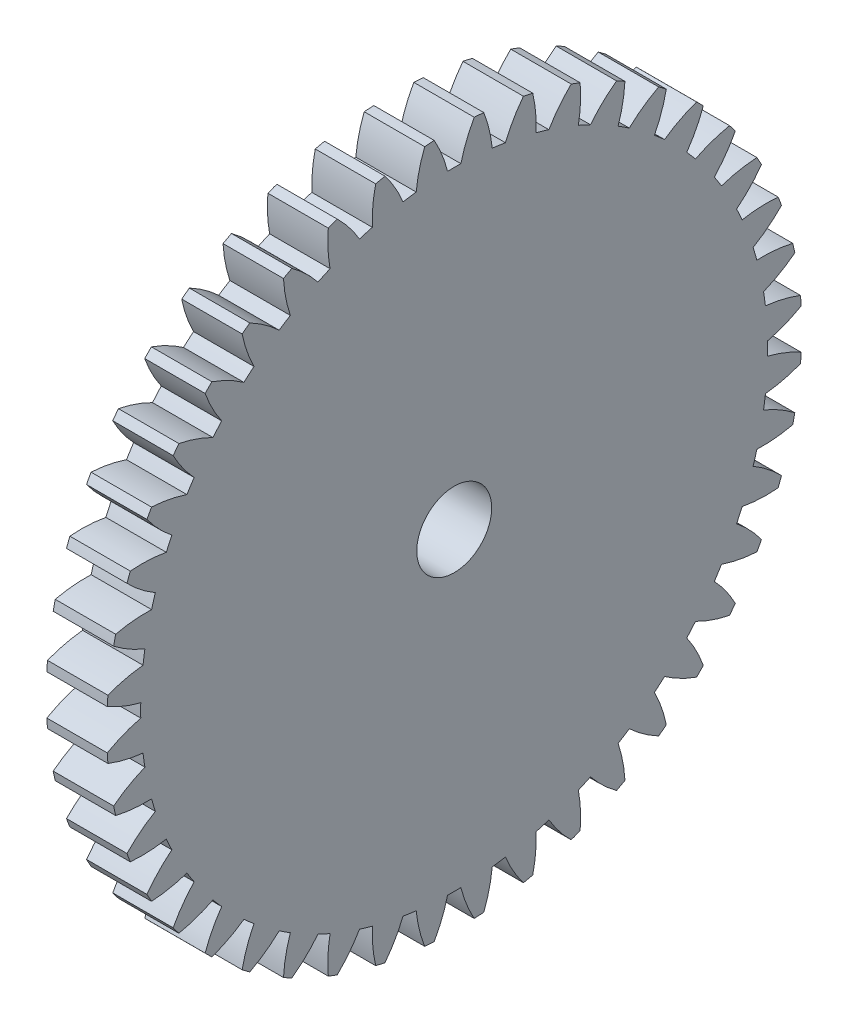
SolidWorks part; units mm, degrees
ref_plane "Front Plane" through (0, 0, 0) normal (0, 0, 1) x (1, 0, 0)
ref_plane "Top Plane" through (0, 0, 0) normal (0, 1, 0) x (1, 0, 0)
ref_plane "Right Plane" through (0, 0, 0) normal (1, 0, 0) x (0, 0, -1)
ref_plane "Plane1" through (3.175, 0, 0) normal (1, 0, 0) x (0, 0, -1)
sketch "Sketch1" plane through (3.175, 0, 0) normal (1, 0, 0) x (0, 0, -1)
  circle A0 centre (-15.8569, 4.6894) radius 0.3969
  arc A1 (-52.3087, 6.7937) -> (-48.7889, 5.3886) centre (-45.4175, 18.9457) ccw
  arc A2 (-48.7889, 5.3886) -> (-48.7889, 3.9902) centre (-15.8569, 4.6894) ccw
  arc A3 (-48.7889, 3.9902) -> (-52.3087, 2.5851) centre (-45.4175, -9.5669) ccw
  arc A4 (-52.3087, 2.5851) -> (-52.2372, 1.5846) centre (-15.8569, 4.6894) ccw
  arc A5 (-52.2372, 1.5846) -> (-48.5532, 0.6948) centre (-47.1455, 14.5937) ccw
  arc A6 (-48.5532, 0.6948) -> (-48.3541, -0.6894) centre (-15.8569, 4.6894) ccw
  arc A7 (-48.3541, -0.6894) -> (-51.6382, -2.5811) centre (-43.0877, -13.6287) ccw
  arc A8 (-51.6382, -2.5811) -> (-51.425, -3.5612) centre (-15.8569, 4.6894) ccw
  arc A9 (-51.425, -3.5612) -> (-47.6519, -3.9177) centre (-48.2366, 10.0401) ccw
  arc A10 (-47.6519, -3.9177) -> (-47.2579, -5.2595) centre (-15.8569, 4.6894) ccw
  arc A11 (-47.2579, -5.2595) -> (-50.2393, -7.5993) centre (-40.2036, -17.3176) ccw
  arc A12 (-50.2393, -7.5993) -> (-49.8888, -8.5391) centre (-15.8569, 4.6894) ccw
  arc A13 (-49.8888, -8.5391) -> (-46.1033, -8.355) centre (-48.6685, 5.3775) ccw
  arc A14 (-46.1033, -8.355) -> (-45.5224, -9.6271) centre (-15.8569, 4.6894) ccw
  arc A15 (-45.5224, -9.6271) -> (-48.1405, -12.3674) centre (-36.8239, -20.5585) ccw
  arc A16 (-48.1405, -12.3674) -> (-47.6598, -13.2477) centre (-15.8569, 4.6894) ccw
  arc A17 (-47.6598, -13.2477) -> (-43.9391, -12.5267) centre (-48.4324, 0.7009) ccw
  arc A18 (-43.9391, -12.5267) -> (-43.183, -13.7032) centre (-15.8569, 4.6894) ccw
  arc A19 (-43.183, -13.7032) -> (-45.3845, -16.7882) centre (-33.0173, -23.2854) ccw
  arc A20 (-45.3845, -16.7882) -> (-44.7834, -17.5912) centre (-15.8569, 4.6894) ccw
  arc A21 (-44.7834, -17.5912) -> (-41.2031, -16.348) centre (-47.5332, -3.8945) ccw
  arc A22 (-41.2031, -16.348) -> (-40.2873, -17.4049) centre (-15.8569, 4.6894) ccw
  arc A23 (-40.2873, -17.4049) -> (-42.0274, -20.7718) centre (-28.8614, -25.4429) ccw
  arc A24 (-42.0274, -20.7718) -> (-41.3181, -21.481) centre (-15.8569, 4.6894) ccw
  arc A25 (-41.3181, -21.481) -> (-37.9512, -19.741) centre (-45.9892, -8.3151) ccw
  arc A26 (-37.9512, -19.741) -> (-36.8943, -20.6568) centre (-15.8569, 4.6894) ccw
  arc A27 (-36.8943, -20.6568) -> (-38.1375, -24.2371) centre (-24.4408, -26.9869) ccw
  arc A28 (-38.1375, -24.2371) -> (-37.3345, -24.8382) centre (-15.8569, 4.6894) ccw
  arc A29 (-37.3345, -24.8382) -> (-34.2495, -22.6367) centre (-43.8318, -12.471) ccw
  arc A30 (-34.2495, -22.6367) -> (-33.073, -23.3927) centre (-15.8569, 4.6894) ccw
  arc A31 (-33.073, -23.3927) -> (-33.794, -27.1135) centre (-19.8454, -27.8861) ccw
  arc A32 (-33.794, -27.1135) -> (-32.9137, -27.5942) centre (-15.8569, 4.6894) ccw
  arc A33 (-32.9137, -27.5942) -> (-30.1734, -24.9761) centre (-41.1048, -16.2776) ccw
  arc A34 (-30.1734, -24.9761) -> (-28.9013, -25.557) centre (-15.8569, 4.6894) ccw
  arc A35 (-28.9013, -25.557) -> (-29.0854, -29.3425) centre (-15.1688, -28.1222) ccw
  arc A36 (-29.0854, -29.3425) -> (-28.1456, -29.693) centre (-15.8569, 4.6894) ccw
  arc A37 (-28.1456, -29.693) -> (-25.8058, -26.7116) centre (-37.8639, -19.6573) ccw
  arc A38 (-25.8058, -26.7116) -> (-24.464, -27.1056) centre (-15.8569, 4.6894) ccw
  arc A39 (-24.464, -27.1056) -> (-24.1075, -30.8787) centre (-10.5063, -27.6903) ccw
  arc A40 (-24.1075, -30.8787) -> (-23.1274, -31.0919) centre (-15.8569, 4.6894) ccw
  arc A41 (-23.1274, -31.0919) -> (-21.2357, -27.8078) centre (-34.175, -22.5414) ccw
  arc A42 (-21.2357, -27.8078) -> (-19.8515, -28.0068) centre (-15.8569, 4.6894) ccw
  arc A43 (-19.8515, -28.0068) -> (-18.9617, -31.6909) centre (-5.9526, -26.5992) ccw
  arc A44 (-18.9617, -31.6909) -> (-17.9612, -31.7624) centre (-15.8569, 4.6894) ccw
  arc A45 (-17.9612, -31.7624) -> (-16.5561, -28.2425) centre (-30.1132, -24.8712) ccw
  arc A46 (-16.5561, -28.2425) -> (-15.1577, -28.2425) centre (-15.8569, 4.6894) ccw
  arc A47 (-15.1577, -28.2425) -> (-13.7526, -31.7624) centre (-1.6006, -24.8712) ccw
  arc A48 (-13.7526, -31.7624) -> (-12.7522, -31.6909) centre (-15.8569, 4.6894) ccw
  arc A49 (-12.7522, -31.6909) -> (-11.8623, -28.0068) centre (-25.7612, -26.5992) ccw
  arc A50 (-11.8623, -28.0068) -> (-10.4781, -27.8078) centre (-15.8569, 4.6894) ccw
  arc A51 (-10.4781, -27.8078) -> (-8.5864, -31.0919) centre (2.4612, -22.5414) ccw
  arc A52 (-8.5864, -31.0919) -> (-7.6063, -30.8787) centre (-15.8569, 4.6894) ccw
  arc A53 (-7.6063, -30.8787) -> (-7.2498, -27.1056) centre (-21.2076, -27.6903) ccw
  arc A54 (-7.2498, -27.1056) -> (-5.908, -26.7116) centre (-15.8569, 4.6894) ccw
  arc A55 (-5.908, -26.7116) -> (-3.5682, -29.693) centre (6.1501, -19.6573) ccw
  arc A56 (-3.5682, -29.693) -> (-2.6284, -29.3425) centre (-15.8569, 4.6894) ccw
  arc A57 (-2.6284, -29.3425) -> (-2.8125, -25.557) centre (-16.545, -28.1222) ccw
  arc A58 (-2.8125, -25.557) -> (-1.5405, -24.9761) centre (-15.8569, 4.6894) ccw
  arc A59 (-1.5405, -24.9761) -> (1.1998, -27.5942) centre (9.391, -16.2776) ccw
  arc A60 (1.1998, -27.5942) -> (2.0802, -27.1135) centre (-15.8569, 4.6894) ccw
  arc A61 (2.0802, -27.1135) -> (1.3592, -23.3927) centre (-11.8684, -27.8861) ccw
  arc A62 (1.3592, -23.3927) -> (2.5356, -22.6367) centre (-15.8569, 4.6894) ccw
  arc A63 (2.5356, -22.6367) -> (5.6207, -24.8382) centre (12.1179, -12.471) ccw
  arc A64 (5.6207, -24.8382) -> (6.4236, -24.2371) centre (-15.8569, 4.6894) ccw
  arc A65 (6.4236, -24.2371) -> (5.1805, -20.6568) centre (-7.2731, -26.9869) ccw
  arc A66 (5.1805, -20.6568) -> (6.2373, -19.741) centre (-15.8569, 4.6894) ccw
  arc A67 (6.2373, -19.741) -> (9.6043, -21.481) centre (14.2754, -8.3151) ccw
  arc A68 (9.6043, -21.481) -> (10.3135, -20.7718) centre (-15.8569, 4.6894) ccw
  arc A69 (10.3135, -20.7718) -> (8.5735, -17.4049) centre (-2.8524, -25.4429) ccw
  arc A70 (8.5735, -17.4049) -> (9.4893, -16.348) centre (-15.8569, 4.6894) ccw
  arc A71 (9.4893, -16.348) -> (13.0695, -17.5912) centre (15.8194, -3.8945) ccw
  arc A72 (13.0695, -17.5912) -> (13.6706, -16.7882) centre (-15.8569, 4.6894) ccw
  arc A73 (13.6706, -16.7882) -> (11.4692, -13.7032) centre (1.3035, -23.2854) ccw
  arc A74 (11.4692, -13.7032) -> (12.2252, -12.5267) centre (-15.8569, 4.6894) ccw
  arc A75 (12.2252, -12.5267) -> (15.946, -13.2477) centre (16.7186, 0.7009) ccw
  arc A76 (15.946, -13.2477) -> (16.4267, -12.3674) centre (-15.8569, 4.6894) ccw
  arc A77 (16.4267, -12.3674) -> (13.8086, -9.6271) centre (5.1101, -20.5585) ccw
  arc A78 (13.8086, -9.6271) -> (14.3895, -8.355) centre (-15.8569, 4.6894) ccw
  arc A79 (14.3895, -8.355) -> (18.175, -8.5391) centre (16.9546, 5.3775) ccw
  arc A80 (18.175, -8.5391) -> (18.5255, -7.5993) centre (-15.8569, 4.6894) ccw
  arc A81 (18.5255, -7.5993) -> (15.544, -5.2595) centre (8.4898, -17.3176) ccw
  arc A82 (15.544, -5.2595) -> (15.938, -3.9177) centre (-15.8569, 4.6894) ccw
  arc A83 (15.938, -3.9177) -> (19.7112, -3.5612) centre (16.5227, 10.0401) ccw
  arc A84 (19.7112, -3.5612) -> (19.9244, -2.5811) centre (-15.8569, 4.6894) ccw
  arc A85 (19.9244, -2.5811) -> (16.6403, -0.6894) centre (11.3739, -13.6287) ccw
  arc A86 (16.6403, -0.6894) -> (16.8393, 0.6948) centre (-15.8569, 4.6894) ccw
  arc A87 (16.8393, 0.6948) -> (20.5233, 1.5846) centre (15.4317, 14.5937) ccw
  arc A88 (20.5233, 1.5846) -> (20.5949, 2.5851) centre (-15.8569, 4.6894) ccw
  arc A89 (20.5949, 2.5851) -> (17.075, 3.9902) centre (13.7037, -9.5669) ccw
  arc A90 (17.075, 3.9902) -> (17.075, 5.3886) centre (-15.8569, 4.6894) ccw
  arc A91 (17.075, 5.3886) -> (20.5949, 6.7937) centre (13.7037, 18.9457) ccw
  arc A92 (20.5949, 6.7937) -> (20.5233, 7.7942) centre (-15.8569, 4.6894) ccw
  arc A93 (20.5233, 7.7942) -> (16.8393, 8.684) centre (15.4317, -5.2149) ccw
  arc A94 (16.8393, 8.684) -> (16.6403, 10.0682) centre (-15.8569, 4.6894) ccw
  arc A95 (16.6403, 10.0682) -> (19.9244, 11.9599) centre (11.3739, 23.0075) ccw
  arc A96 (19.9244, 11.9599) -> (19.7112, 12.94) centre (-15.8569, 4.6894) ccw
  arc A97 (19.7112, 12.94) -> (15.938, 13.2965) centre (16.5227, -0.6613) ccw
  arc A98 (15.938, 13.2965) -> (15.544, 14.6383) centre (-15.8569, 4.6894) ccw
  arc A99 (15.544, 14.6383) -> (18.5255, 16.9781) centre (8.4898, 26.6964) ccw
  arc A100 (18.5255, 16.9781) -> (18.175, 17.9179) centre (-15.8569, 4.6894) ccw
  arc A101 (18.175, 17.9179) -> (14.3895, 17.7338) centre (16.9546, 4.0013) ccw
  arc A102 (14.3895, 17.7338) -> (13.8086, 19.0058) centre (-15.8569, 4.6894) ccw
  arc A103 (13.8086, 19.0058) -> (16.4267, 21.7461) centre (5.1101, 29.9373) ccw
  arc A104 (16.4267, 21.7461) -> (15.946, 22.6265) centre (-15.8569, 4.6894) ccw
  arc A105 (15.946, 22.6265) -> (12.2252, 21.9055) centre (16.7186, 8.6779) ccw
  arc A106 (12.2252, 21.9055) -> (11.4692, 23.082) centre (-15.8569, 4.6894) ccw
  arc A107 (11.4692, 23.082) -> (13.6706, 26.167) centre (1.3035, 32.6642) ccw
  arc A108 (13.6706, 26.167) -> (13.0695, 26.9699) centre (-15.8569, 4.6894) ccw
  arc A109 (13.0695, 26.9699) -> (9.4893, 25.7268) centre (15.8194, 13.2733) ccw
  arc A110 (9.4893, 25.7268) -> (8.5735, 26.7837) centre (-15.8569, 4.6894) ccw
  arc A111 (8.5735, 26.7837) -> (10.3135, 30.1506) centre (-2.8524, 34.8217) ccw
  arc A112 (10.3135, 30.1506) -> (9.6043, 30.8598) centre (-15.8569, 4.6894) ccw
  arc A113 (9.6043, 30.8598) -> (6.2373, 29.1198) centre (14.2754, 17.6939) ccw
  arc A114 (6.2373, 29.1198) -> (5.1805, 30.0356) centre (-15.8569, 4.6894) ccw
  arc A115 (5.1805, 30.0356) -> (6.4236, 33.6158) centre (-7.2731, 36.3657) ccw
  arc A116 (6.4236, 33.6158) -> (5.6207, 34.2169) centre (-15.8569, 4.6894) ccw
  arc A117 (5.6207, 34.2169) -> (2.5356, 32.0155) centre (12.1179, 21.8498) ccw
  arc A118 (2.5356, 32.0155) -> (1.3592, 32.7715) centre (-15.8569, 4.6894) ccw
  arc A119 (1.3592, 32.7715) -> (2.0802, 36.4923) centre (-11.8684, 37.2649) ccw
  arc A120 (2.0802, 36.4923) -> (1.1998, 36.973) centre (-15.8569, 4.6894) ccw
  arc A121 (1.1998, 36.973) -> (-1.5405, 34.3549) centre (9.391, 25.6564) ccw
  arc A122 (-1.5405, 34.3549) -> (-2.8125, 34.9358) centre (-15.8569, 4.6894) ccw
  arc A123 (-2.8125, 34.9358) -> (-2.6284, 38.7213) centre (-16.545, 37.5009) ccw
  arc A124 (-2.6284, 38.7213) -> (-3.5682, 39.0718) centre (-15.8569, 4.6894) ccw
  arc A125 (-3.5682, 39.0718) -> (-5.908, 36.0904) centre (6.1501, 29.0361) ccw
  arc A126 (-5.908, 36.0904) -> (-7.2498, 36.4843) centre (-15.8569, 4.6894) ccw
  arc A127 (-7.2498, 36.4843) -> (-7.6063, 40.2575) centre (-21.2076, 37.069) ccw
  arc A128 (-7.6063, 40.2575) -> (-8.5864, 40.4707) centre (-15.8569, 4.6894) ccw
  arc A129 (-8.5864, 40.4707) -> (-10.4781, 37.1866) centre (2.4612, 31.9202) ccw
  arc A130 (-10.4781, 37.1866) -> (-11.8623, 37.3856) centre (-15.8569, 4.6894) ccw
  arc A131 (-11.8623, 37.3856) -> (-12.7522, 41.0697) centre (-25.7612, 35.978) ccw
  arc A132 (-12.7522, 41.0697) -> (-13.7526, 41.1412) centre (-15.8569, 4.6894) ccw
  arc A133 (-13.7526, 41.1412) -> (-15.1577, 37.6213) centre (-1.6006, 34.25) ccw
  arc A134 (-15.1577, 37.6213) -> (-16.5561, 37.6213) centre (-15.8569, 4.6894) ccw
  arc A135 (-16.5561, 37.6213) -> (-17.9612, 41.1412) centre (-30.1132, 34.25) ccw
  arc A136 (-17.9612, 41.1412) -> (-18.9617, 41.0697) centre (-15.8569, 4.6894) ccw
  arc A137 (-18.9617, 41.0697) -> (-19.8515, 37.3856) centre (-5.9526, 35.978) ccw
  arc A138 (-19.8515, 37.3856) -> (-21.2357, 37.1866) centre (-15.8569, 4.6894) ccw
  arc A139 (-21.2357, 37.1866) -> (-23.1274, 40.4707) centre (-34.175, 31.9202) ccw
  arc A140 (-23.1274, 40.4707) -> (-24.1075, 40.2575) centre (-15.8569, 4.6894) ccw
  arc A141 (-24.1075, 40.2575) -> (-24.464, 36.4843) centre (-10.5063, 37.069) ccw
  arc A142 (-24.464, 36.4843) -> (-25.8058, 36.0904) centre (-15.8569, 4.6894) ccw
  arc A143 (-25.8058, 36.0904) -> (-28.1456, 39.0718) centre (-37.8639, 29.0361) ccw
  arc A144 (-28.1456, 39.0718) -> (-29.0854, 38.7213) centre (-15.8569, 4.6894) ccw
  arc A145 (-29.0854, 38.7213) -> (-28.9013, 34.9358) centre (-15.1688, 37.5009) ccw
  arc A146 (-28.9013, 34.9358) -> (-30.1734, 34.3549) centre (-15.8569, 4.6894) ccw
  arc A147 (-30.1734, 34.3549) -> (-32.9137, 36.973) centre (-41.1048, 25.6564) ccw
  arc A148 (-32.9137, 36.973) -> (-33.794, 36.4923) centre (-15.8569, 4.6894) ccw
  arc A149 (-33.794, 36.4923) -> (-33.073, 32.7715) centre (-19.8454, 37.2649) ccw
  arc A150 (-33.073, 32.7715) -> (-34.2495, 32.0155) centre (-15.8569, 4.6894) ccw
  arc A151 (-34.2495, 32.0155) -> (-37.3345, 34.2169) centre (-43.8318, 21.8498) ccw
  arc A152 (-37.3345, 34.2169) -> (-38.1375, 33.6158) centre (-15.8569, 4.6894) ccw
  arc A153 (-38.1375, 33.6158) -> (-36.8943, 30.0356) centre (-24.4408, 36.3657) ccw
  arc A154 (-36.8943, 30.0356) -> (-37.9512, 29.1198) centre (-15.8569, 4.6894) ccw
  arc A155 (-37.9512, 29.1198) -> (-41.3181, 30.8598) centre (-45.9892, 17.6939) ccw
  arc A156 (-41.3181, 30.8598) -> (-42.0274, 30.1506) centre (-15.8569, 4.6894) ccw
  arc A157 (-42.0274, 30.1506) -> (-40.2873, 26.7837) centre (-28.8614, 34.8217) ccw
  arc A158 (-40.2873, 26.7837) -> (-41.2031, 25.7268) centre (-15.8569, 4.6894) ccw
  arc A159 (-41.2031, 25.7268) -> (-44.7834, 26.9699) centre (-47.5332, 13.2733) ccw
  arc A160 (-44.7834, 26.9699) -> (-45.3845, 26.167) centre (-15.8569, 4.6894) ccw
  arc A161 (-45.3845, 26.167) -> (-43.183, 23.082) centre (-33.0173, 32.6642) ccw
  arc A162 (-43.183, 23.082) -> (-43.9391, 21.9055) centre (-15.8569, 4.6894) ccw
  arc A163 (-43.9391, 21.9055) -> (-47.6598, 22.6265) centre (-48.4324, 8.6779) ccw
  arc A164 (-47.6598, 22.6265) -> (-48.1405, 21.7461) centre (-15.8569, 4.6894) ccw
  arc A165 (-48.1405, 21.7461) -> (-45.5224, 19.0058) centre (-36.8239, 29.9373) ccw
  arc A166 (-45.5224, 19.0058) -> (-46.1033, 17.7338) centre (-15.8569, 4.6894) ccw
  arc A167 (-46.1033, 17.7338) -> (-49.8888, 17.9179) centre (-48.6685, 4.0013) ccw
  arc A168 (-49.8888, 17.9179) -> (-50.2393, 16.9781) centre (-15.8569, 4.6894) ccw
  arc A169 (-50.2393, 16.9781) -> (-47.2579, 14.6383) centre (-40.2036, 26.6964) ccw
  arc A170 (-47.2579, 14.6383) -> (-47.6519, 13.2965) centre (-15.8569, 4.6894) ccw
  arc A171 (-47.6519, 13.2965) -> (-51.425, 12.94) centre (-48.2366, -0.6613) ccw
  arc A172 (-51.425, 12.94) -> (-51.6382, 11.9599) centre (-15.8569, 4.6894) ccw
  arc A173 (-51.6382, 11.9599) -> (-48.3541, 10.0682) centre (-43.0877, 23.0075) ccw
  arc A174 (-48.3541, 10.0682) -> (-48.5532, 8.684) centre (-15.8569, 4.6894) ccw
  arc A175 (-48.5532, 8.684) -> (-52.2372, 7.7942) centre (-47.1455, -5.2149) ccw
  arc A176 (-52.2372, 7.7942) -> (-52.3087, 6.7937) centre (-15.8569, 4.6894) ccw
extrude "Boss-Extrude1" add sketch "Sketch1" against normal blind 6.35
sketch "Sketch2" plane through (3.175, 0, 0) normal (1, 0, 0) x (0, 0, -1)
  circle A0 centre (-15.8569, 4.6894) radius 3.937
  dimension "D1" = 7.874
extrude "Cut-Extrude1" cut sketch "Sketch2" against normal through all both and the other way through all
